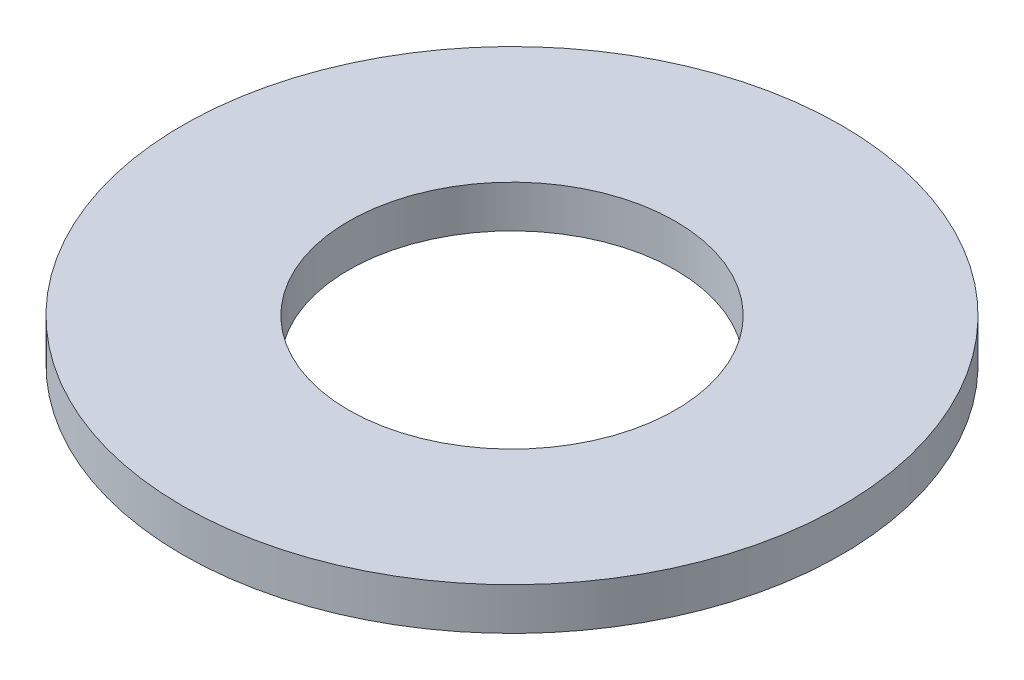
SolidWorks part; units mm, degrees
ref_plane "Front Plane" through (0, 0, 0) normal (0, 0, 1) x (1, 0, 0)
ref_plane "Top Plane" through (0, 0, 0) normal (0, 1, 0) x (1, 0, 0)
ref_plane "Right Plane" through (0, 0, 0) normal (1, 0, 0) x (0, 0, -1)
sketch "Sketch1" plane through (0, 0, 0) normal (0, 1, 0) x (1, 0, 0)
  circle A0 centre (0, 0) radius 3.175
  circle A1 centre (0, 0) radius 6.4
  dimension "D1" = 6.35
  dimension "D2" = 12.8
extrude "Boss-Extrude1" add sketch "Sketch1" along normal blind 0.82
